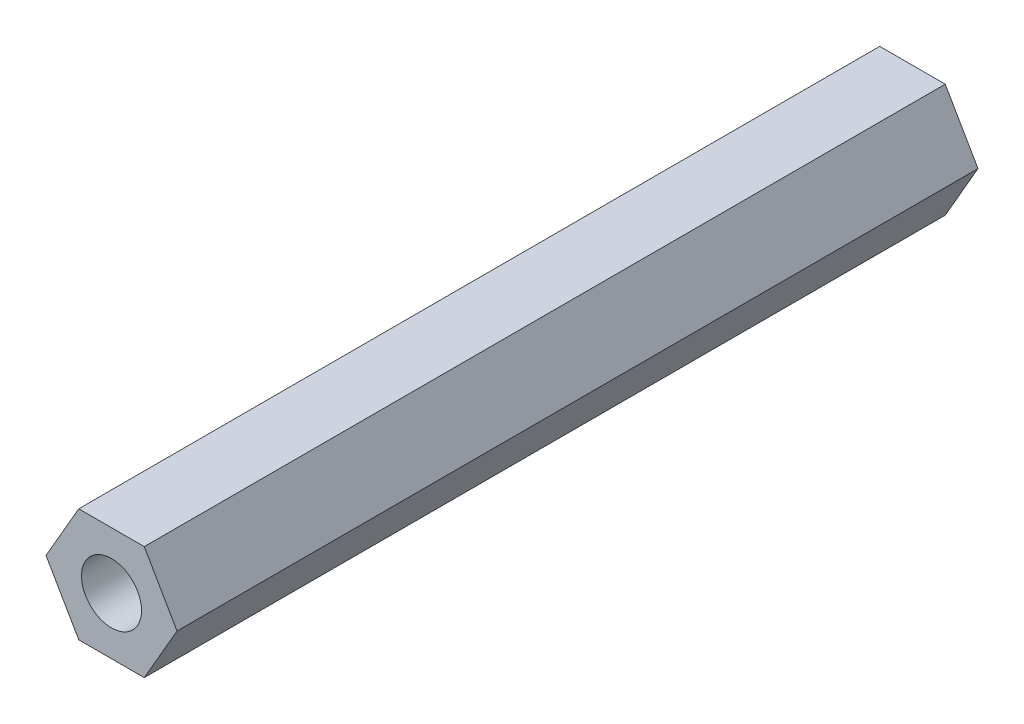
SolidWorks part; units mm, degrees
ref_plane "Alzado" through (0, 0, 0) normal (0, 0, 1) x (1, 0, 0)
ref_plane "Planta" through (0, 0, 0) normal (0, 1, 0) x (1, 0, 0)
ref_plane "Vista lateral" through (0, 0, 0) normal (1, 0, 0) x (0, 0, -1)
sketch "Croquis1" plane through (0, 0, 0) normal (0, 0, 1) x (1, 0, 0)
  line L1 (4.9075, 0) -> (2.4537, 4.25)
  line L2 (2.4537, 4.25) -> (-2.4537, 4.25)
  line L3 (-2.4537, 4.25) -> (-4.9075, 0)
  line L4 (-4.9075, 0) -> (-2.4537, -4.25)
  line L5 (-2.4537, -4.25) -> (2.4537, -4.25)
  line L6 (2.4537, -4.25) -> (4.9075, 0)
  circle A0 centre (0, 0) radius 2.25
  circle A1 centre (0, 0) radius 4.25 construction
  dimension "D1" = 4.5
  dimension "D2" = 2
extrude "Saliente-Extruir1" add sketch "Croquis1" along normal blind 60
